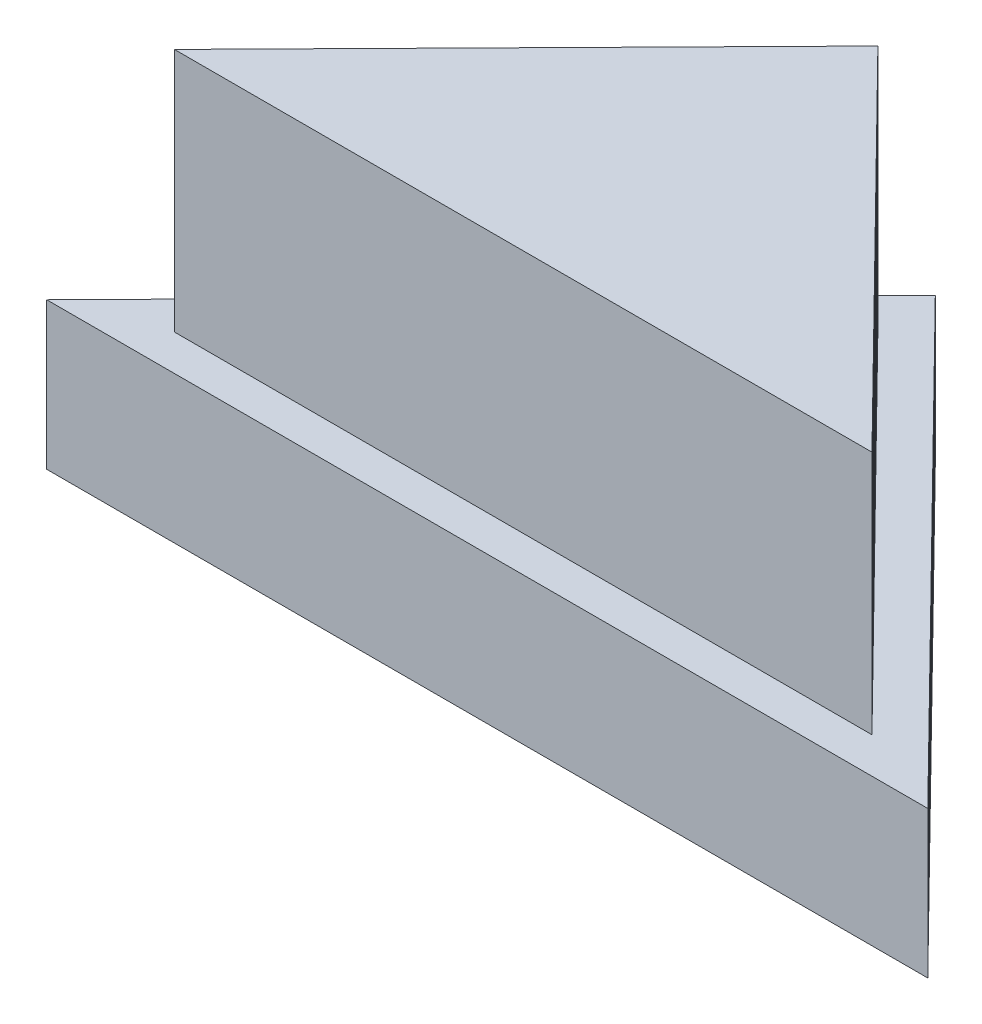
SolidWorks part; units mm, degrees
ref_plane "Front Plane" through (0, 0, 0) normal (0, 0, 1) x (1, 0, 0)
ref_plane "Top Plane" through (0, 0, 0) normal (0, 1, 0) x (1, 0, 0)
ref_plane "Right Plane" through (0, 0, 0) normal (1, 0, 0) x (0, 0, -1)
sketch "Sketch1" plane through (0, 0, 0) normal (0, 1, 0) x (1, 0, 0)
  point P1 (0, 0)
  point P2 (0, 0)
  point P14 (0, 0)
  point P16 (0, 0)
  point P17 (0, 0)
  line B0 (8.9833, -8.3971) -> (-9.0167, -8.3971)
  line B1 (-0.0167, 0.7563) -> (-9.0167, -8.3971)
  line B2 (8.9833, -8.3971) -> (-0.0167, 0.7563)
sketch_block_instance "Block1-1"
sketch_block "Block1"
extrude "Boss-Extrude1" add sketch "Sketch1" along normal blind 3
sketch "Sketch2" plane through (0, 3, 0) normal (0, 1, 0) x (1, 0, 0)
  line L3 (-0.0167, 0.7563) -> (-0.0167, -8.3971) construction
  line L4 (-9.0167, -8.3971) -> (8.9833, -8.3971) construction
  line L5 (-0.0167, -3.8204) -> (-9.0167, -8.3971) construction
  line L6 (8.9833, -8.3971) -> (-0.0167, -3.8204) construction
  point P10 (0, 0)
  line B0 (7.109, -7.6634) -> (-0.016, -0.4169)
  line B1 (7.109, -7.6634) -> (-7.1411, -7.6634)
  line B2 (-7.1411, -7.6634) -> (-0.016, -0.4169)
sketch_block_instance "Block2-1"
sketch_block "Block2"
extrude "Boss-Extrude2" add sketch "Sketch2" along normal blind 5
sketch "Sketch3" plane through (0, 0, 0) normal (0, -1, 0) x (1, 0, 0)
  line L0 (-0.0167, -0.7563) -> (-0.0167, 8.3971) construction
  line L1 (-9.0167, 8.3971) -> (8.9833, 8.3971) construction
  line L2 (4.4833, 3.8204) -> (-9.0167, 8.3971) construction
  line L3 (8.9833, 8.3971) -> (-0.0167, -0.7563) construction
  line L4 (-4.5167, 3.8204) -> (8.9833, 8.3971) construction
  line L5 (-0.0167, -0.7563) -> (-9.0167, 8.3971) construction
  circle A0 centre (-0.0167, 5.346) radius 1.8
  dimension "D1" = 3.6
extrude "Cut-Extrude1" cut sketch "Sketch3" against normal blind 1
